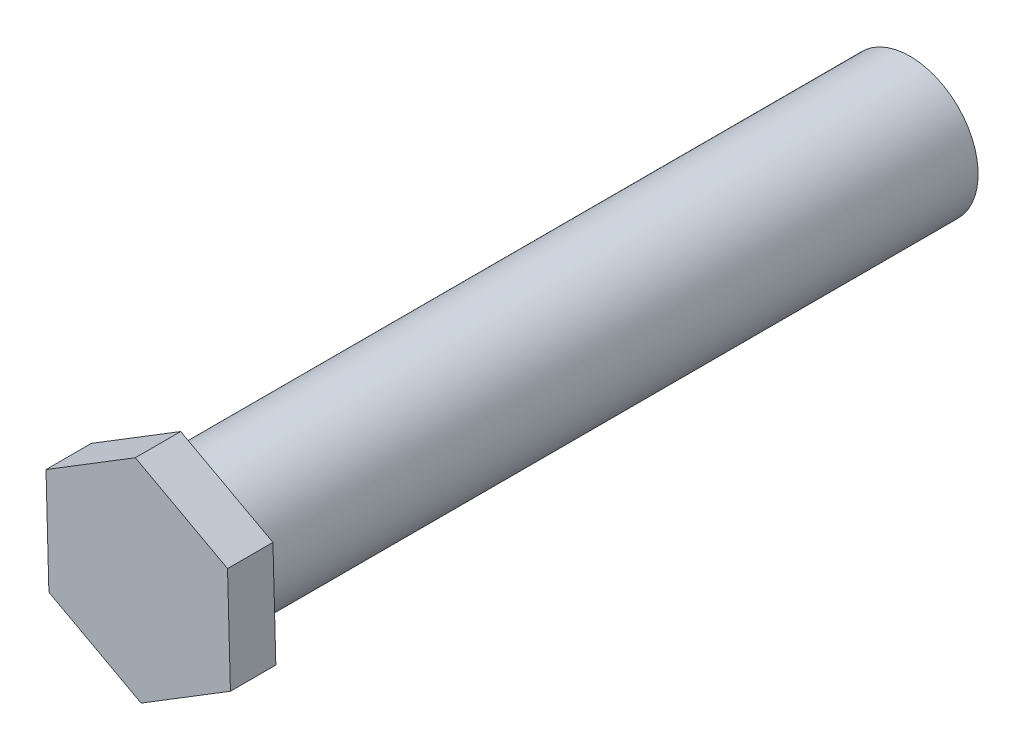
SolidWorks part; units mm, degrees
ref_plane "Front Plane" through (0, 0, 0) normal (0, 0, 1) x (1, 0, 0)
ref_plane "Top Plane" through (0, 0, 0) normal (0, 1, 0) x (1, 0, 0)
ref_plane "Right Plane" through (0, 0, 0) normal (1, 0, 0) x (0, 0, -1)
sketch "Sketch2" plane through (0, 0, 0) normal (0, 0, 1) x (1, 0, 0)
  line L1 (3.9347, 2.4189) -> (-0.1275, 4.617)
  line L2 (-0.1275, 4.617) -> (-4.0622, 2.1981)
  line L3 (-4.0622, 2.1981) -> (-3.9347, -2.4189)
  line L4 (-3.9347, -2.4189) -> (0.1275, -4.617)
  line L5 (0.1275, -4.617) -> (4.0622, -2.1981)
  line L6 (4.0622, -2.1981) -> (3.9347, 2.4189)
  circle A0 centre (0, 0) radius 4 construction
  dimension "D1" = 8
extrude "Boss-Extrude1" add sketch "Sketch2" along normal blind 2
sketch "Sketch4" plane through (0, 0, 0) normal (0, 0, -1) x (-1, 0, 0)
  circle A0 centre (0, 0) radius 3
extrude "Boss-Extrude2" add sketch "Sketch4" along normal blind 32
